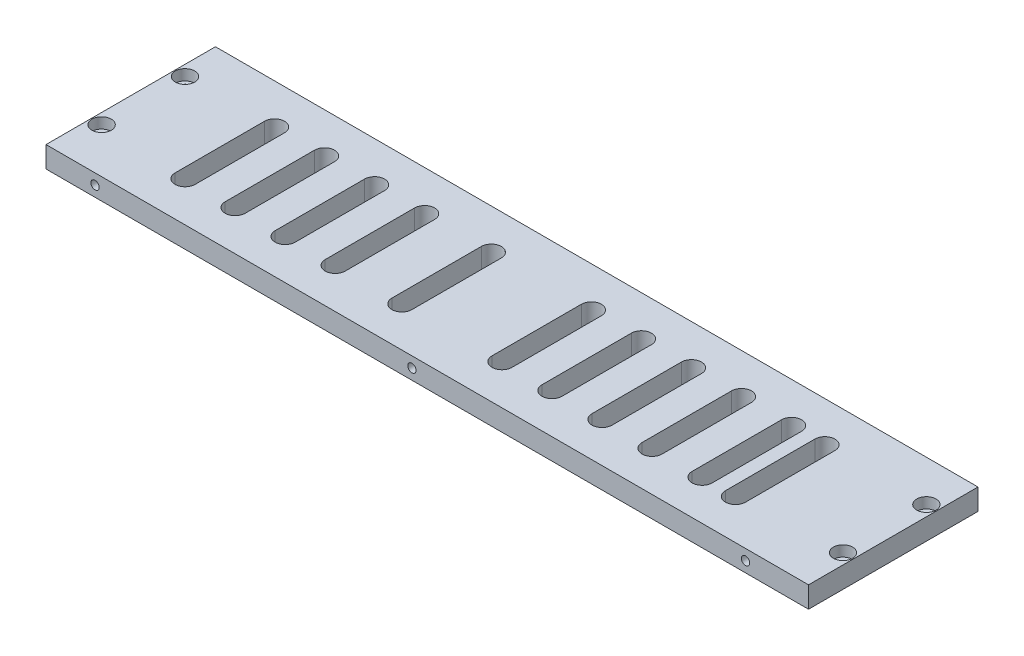
SolidWorks part; units mm, degrees
material "Aleación 6061"
ref_plane "Alzado" through (0, 0, 0) normal (0, 0, 1) x (1, 0, 0)
ref_plane "Planta" through (0, 0, 0) normal (0, 1, 0) x (1, 0, 0)
ref_plane "Vista lateral" through (0, 0, 0) normal (1, 0, 0) x (0, 0, -1)
sketch "Croquis1" plane through (0, 0, 0) normal (0, 1, 0) x (1, 0, 0)
  line L1 (-139.7, -12.7) -> (88.9, -12.7)
  line L2 (-139.7, -12.7) -> (-139.7, -63.5)
  line L3 (-139.7, -63.5) -> (88.9, -63.5)
  line L4 (88.9, -12.7) -> (88.9, -63.5)
  dimension "D1" = 139.7
  dimension "D2" = 12.7
  dimension "D3" = 88.9
  dimension "D4" = 12.7
  dimension "D5" = 139.7
  dimension "D6" = 63.5
  dimension "D7" = 88.9
  dimension "D8" = 63.5
extrude "Pared_+Y_1-4in" add sketch "Croquis1" along normal blind 6.35 from offset 95.25
sketch "Croquis2" plane through (0, 0, 0) normal (0, 0, 1) x (1, 0, 0)
  circle A0 centre (-125, 98.425) radius 1.25
  circle A1 centre (-30, 98.425) radius 1.25
  circle A2 centre (70, 98.425) radius 1.25
  dimension "D1" = 2.5
  dimension "D2" = 2.5
  dimension "D3" = 2.5
  dimension "D4" = 125
  dimension "D5" = 98.425
  dimension "D6" = 30
  dimension "D7" = 98.425
  dimension "D8" = 70
  dimension "D9" = 98.425
extrude "Rosca_M3_inferior" cut sketch "Croquis2" along normal blind 10 from offset 12.7
sketch "Croquis3" plane through (0, 0, 0) normal (0, 0, 1) x (1, 0, 0)
  circle A0 centre (-125, 98.425) radius 1.25
  circle A1 centre (-30, 98.425) radius 1.25
  circle A2 centre (70, 98.425) radius 1.25
  dimension "D1" = 2.5
  dimension "D2" = 2.5
  dimension "D3" = 2.5
  dimension "D4" = 125
  dimension "D5" = 98.425
  dimension "D6" = 30
  dimension "D7" = 98.425
  dimension "D8" = 70
  dimension "D9" = 98.425
extrude "Rosca_M3_superior" cut sketch "Croquis3" along normal blind 10 from offset 53.5
sketch "Croquis4" plane through (0, 0, 0) normal (0, 1, 0) x (1, 0, 0)
  circle A0 centre (-136.525, -25) radius 1.7
  circle A1 centre (-136.525, -50) radius 1.7
  circle A2 centre (85.725, -25) radius 1.7
  circle A3 centre (85.725, -50) radius 1.7
  dimension "D1" = 3.4
  dimension "D2" = 3.4
  dimension "D3" = 3.4
  dimension "D4" = 3.4
  dimension "D5" = 136.525
  dimension "D6" = 25
  dimension "D7" = 136.525
  dimension "D8" = 50
  dimension "D9" = 85.725
  dimension "D10" = 25
  dimension "D11" = 85.725
  dimension "D12" = 50
extrude "Barrenos_M3_esquinas" cut sketch "Croquis4" along normal blind 6.35 from offset 95.25
sketch "Croquis5" plane through (0, 0, 0) normal (0, 1, 0) x (1, 0, 0)
  circle A0 centre (-136.525, -25) radius 2.9
  circle A1 centre (-136.525, -50) radius 2.9
  circle A2 centre (85.725, -25) radius 2.9
  circle A3 centre (85.725, -50) radius 2.9
  dimension "D1" = 5.8
  dimension "D2" = 5.8
  dimension "D3" = 5.8
  dimension "D4" = 5.8
  dimension "D5" = 136.525
  dimension "D6" = 25
  dimension "D7" = 136.525
  dimension "D8" = 50
  dimension "D9" = 85.725
  dimension "D10" = 25
  dimension "D11" = 85.725
  dimension "D12" = 50
extrude "Refrentado_M3_esquinas" cut sketch "Croquis5" along normal blind 3.2 from offset 98.4
sketch "Croquis6" plane through (0, 0, 0) normal (0, 1, 0) x (1, 0, 0)
  line L0 (-107, -24.7) -> (-107, -51.5)
  line L1 (-113, -51.5) -> (-113, -24.7)
  line L2 (-92, -24.7) -> (-92, -51.5)
  line L3 (-98, -51.5) -> (-98, -24.7)
  line L4 (-77, -24.7) -> (-77, -51.5)
  line L5 (-83, -51.5) -> (-83, -24.7)
  line L6 (-62, -24.7) -> (-62, -51.5)
  line L7 (-68, -51.5) -> (-68, -24.7)
  line L8 (-42, -24.7) -> (-42, -51.5)
  line L9 (-48, -51.5) -> (-48, -24.7)
  line L10 (-12, -24.7) -> (-12, -51.5)
  line L11 (-18, -51.5) -> (-18, -24.7)
  line L12 (3, -24.7) -> (3, -51.5)
  line L13 (-3, -51.5) -> (-3, -24.7)
  line L14 (18, -24.7) -> (18, -51.5)
  line L15 (12, -51.5) -> (12, -24.7)
  line L16 (33, -24.7) -> (33, -51.5)
  line L17 (27, -51.5) -> (27, -24.7)
  line L18 (48, -24.7) -> (48, -51.5)
  line L19 (42, -51.5) -> (42, -24.7)
  line L20 (58, -24.7) -> (58, -51.5)
  line L21 (52, -51.5) -> (52, -24.7)
  arc A0 (-107, -51.5) -> (-113, -51.5) centre (-110, -51.5) cw
  arc A1 (-113, -24.7) -> (-107, -24.7) centre (-110, -24.7) cw
  arc A2 (-92, -51.5) -> (-98, -51.5) centre (-95, -51.5) cw
  arc A3 (-98, -24.7) -> (-92, -24.7) centre (-95, -24.7) cw
  arc A4 (-77, -51.5) -> (-83, -51.5) centre (-80, -51.5) cw
  arc A5 (-83, -24.7) -> (-77, -24.7) centre (-80, -24.7) cw
  arc A6 (-62, -51.5) -> (-68, -51.5) centre (-65, -51.5) cw
  arc A7 (-68, -24.7) -> (-62, -24.7) centre (-65, -24.7) cw
  arc A8 (-42, -51.5) -> (-48, -51.5) centre (-45, -51.5) cw
  arc A9 (-48, -24.7) -> (-42, -24.7) centre (-45, -24.7) cw
  arc A10 (-12, -51.5) -> (-18, -51.5) centre (-15, -51.5) cw
  arc A11 (-18, -24.7) -> (-12, -24.7) centre (-15, -24.7) cw
  arc A12 (3, -51.5) -> (-3, -51.5) centre (0, -51.5) cw
  arc A13 (-3, -24.7) -> (3, -24.7) centre (0, -24.7) cw
  arc A14 (18, -51.5) -> (12, -51.5) centre (15, -51.5) cw
  arc A15 (12, -24.7) -> (18, -24.7) centre (15, -24.7) cw
  arc A16 (33, -51.5) -> (27, -51.5) centre (30, -51.5) cw
  arc A17 (27, -24.7) -> (33, -24.7) centre (30, -24.7) cw
  arc A18 (48, -51.5) -> (42, -51.5) centre (45, -51.5) cw
  arc A19 (42, -24.7) -> (48, -24.7) centre (45, -24.7) cw
  arc A20 (58, -51.5) -> (52, -51.5) centre (55, -51.5) cw
  arc A21 (52, -24.7) -> (58, -24.7) centre (55, -24.7) cw
  dimension "D1" = 3
  dimension "D2" = 3
  dimension "D3" = 3
  dimension "D4" = 3
  dimension "D5" = 3
  dimension "D6" = 3
  dimension "D7" = 3
  dimension "D8" = 3
  dimension "D9" = 3
  dimension "D10" = 3
  dimension "D11" = 3
  dimension "D12" = 3
  dimension "D13" = 3
  dimension "D14" = 3
  dimension "D15" = 3
  dimension "D16" = 3
  dimension "D17" = 3
  dimension "D18" = 3
  dimension "D19" = 3
  dimension "D20" = 3
  dimension "D21" = 3
  dimension "D22" = 3
  dimension "D23" = 107
  dimension "D24" = 24.7
  dimension "D25" = 107
  dimension "D26" = 51.5
  dimension "D27" = 113
  dimension "D28" = 51.5
  dimension "D29" = 113
  dimension "D30" = 24.7
  dimension "D31" = 92
  dimension "D32" = 24.7
  dimension "D33" = 92
  dimension "D34" = 51.5
  dimension "D35" = 98
  dimension "D36" = 51.5
  dimension "D37" = 98
  dimension "D38" = 24.7
  dimension "D39" = 77
  dimension "D40" = 24.7
  dimension "D41" = 77
  dimension "D42" = 51.5
  dimension "D43" = 83
  dimension "D44" = 51.5
  dimension "D45" = 83
  dimension "D46" = 24.7
  dimension "D47" = 62
  dimension "D48" = 24.7
  dimension "D49" = 62
  dimension "D50" = 51.5
  dimension "D51" = 68
  dimension "D52" = 51.5
  dimension "D53" = 68
  dimension "D54" = 24.7
  dimension "D55" = 42
  dimension "D56" = 24.7
  dimension "D57" = 42
  dimension "D58" = 51.5
  dimension "D59" = 48
  dimension "D60" = 51.5
  dimension "D61" = 48
  dimension "D62" = 24.7
  dimension "D63" = 12
  dimension "D64" = 24.7
  dimension "D65" = 12
  dimension "D66" = 51.5
  dimension "D67" = 18
  dimension "D68" = 51.5
  dimension "D69" = 18
  dimension "D70" = 24.7
  dimension "D71" = 3
  dimension "D72" = 24.7
  dimension "D73" = 3
  dimension "D74" = 51.5
  dimension "D75" = 3
  dimension "D76" = 51.5
  dimension "D77" = 3
  dimension "D78" = 24.7
  dimension "D79" = 18
  dimension "D80" = 24.7
  dimension "D81" = 18
  dimension "D82" = 51.5
  dimension "D83" = 12
  dimension "D84" = 51.5
  dimension "D85" = 12
  dimension "D86" = 24.7
  dimension "D87" = 33
  dimension "D88" = 24.7
  dimension "D89" = 33
  dimension "D90" = 51.5
  dimension "D91" = 27
  dimension "D92" = 51.5
  dimension "D93" = 27
  dimension "D94" = 24.7
  dimension "D95" = 48
  dimension "D96" = 24.7
  dimension "D97" = 48
  dimension "D98" = 51.5
  dimension "D99" = 42
  dimension "D100" = 51.5
  dimension "D101" = 42
  dimension "D102" = 24.7
  dimension "D103" = 58
  dimension "D104" = 24.7
  dimension "D105" = 58
  dimension "D106" = 51.5
  dimension "D107" = 52
  dimension "D108" = 51.5
  dimension "D109" = 52
  dimension "D110" = 24.7
extrude "Ranuras_ventilacion" cut sketch "Croquis6" along normal blind 6.35 from offset 95.25
